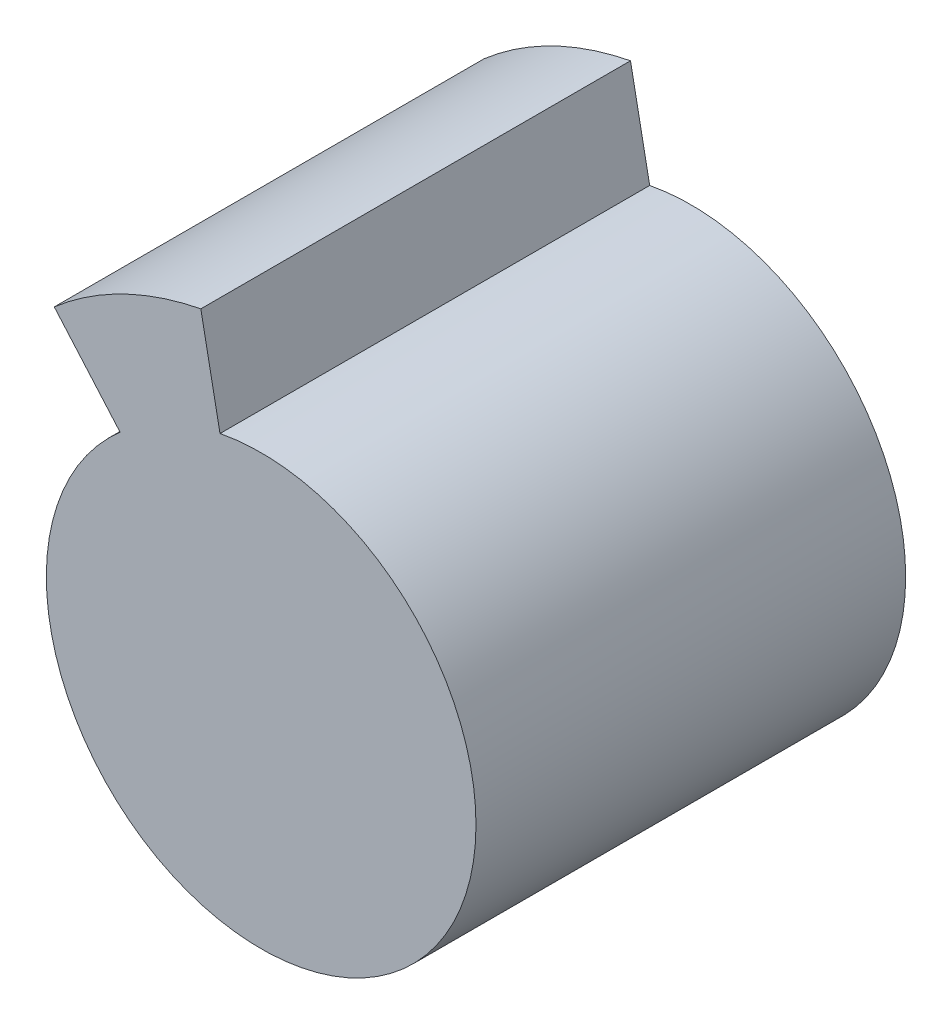
SolidWorks part; units mm, degrees
ref_plane "前视基准面" through (0, 0, 0) normal (0, 0, 1) x (1, 0, 0)
ref_plane "上视基准面" through (0, 0, 0) normal (0, 1, 0) x (1, 0, 0)
ref_plane "右视基准面" through (0, 0, 0) normal (1, 0, 0) x (0, 0, -1)
other "Configuration Table"
sketch "草图1" plane through (0, 0, 0) normal (0, 0, 1) x (1, 0, 0)
  line L0 (-24.4539, 13.3696) -> (-38.8986, 29.9632)
  line L1 (-24.4539, 13.3696) -> (-28.6666, 34.9624)
  circle A0 centre (-24.4539, 13.3696) radius 15
  circle A1 centre (-24.4539, 13.3696) radius 22
  dimension "D1" = 30
  dimension "D2" = 30
  dimension "D3" = 44
extrude "凸台-拉伸1" add sketch "草图1" along normal blind 30 contours L0 A0 L1 | L1 A0 L0 | L1 A1 L0 A0
